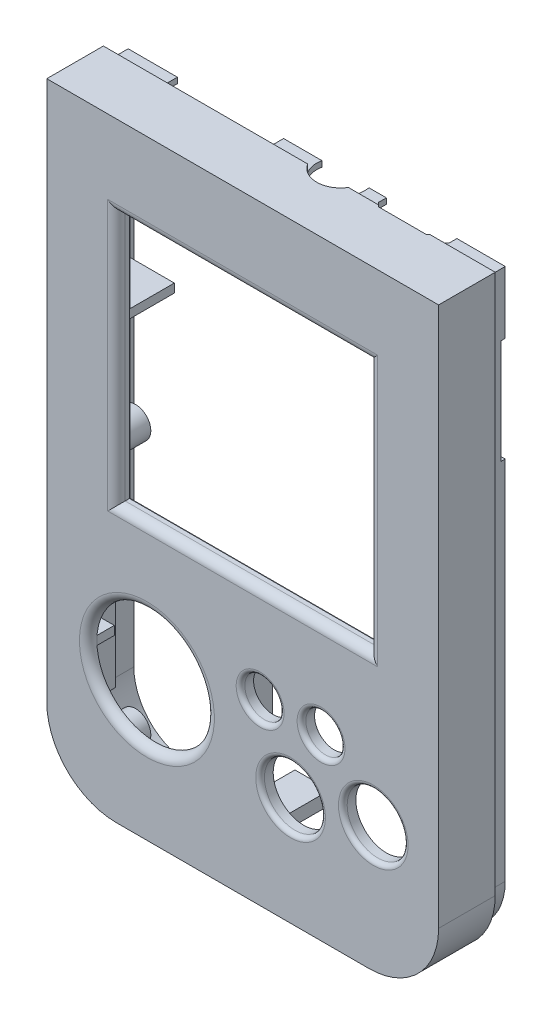
SolidWorks part; units mm, degrees
ref_plane "前视基准面" through (0, 0, 0) normal (0, 0, 1) x (1, 0, 0)
ref_plane "上视基准面" through (0, 0, 0) normal (0, 1, 0) x (1, 0, 0)
ref_plane "右视基准面" through (0, 0, 0) normal (1, 0, 0) x (0, 0, -1)
sketch "草图1" plane through (0, 0, 0) normal (0, 0, 1) x (1, 0, 0)
  line L1 (-45, 70) -> (0, 70)
  line L2 (-45, 70) -> (-45, 8)
  line L3 (-37, 0) -> (-8, 0)
  line L4 (0, 70) -> (0, 8)
  arc A2 (-37, 0) -> (-45, 8) centre (-37, 8) cw
  arc A3 (-8, 0) -> (0, 8) centre (-8, 8) ccw
  point P7 (0, 70)
  point P9 (-45, 0)
  point P10 (-45, 70)
  point P13 (0, 0)
  dimension "D3" = 8
  dimension "D1" = 45
  dimension "D2" = 70
extrude "凸台-拉伸1" add sketch "草图1" along normal blind 8.5 contours L1 L4 A3 L3 A2 L2
shell "抽壳2" thickness 1.5
sketch "草图4" plane through (0, 0, 0) normal (0, 0, -1) x (-1, 0, 0)
  line L0 (22.5, 68.5) -> (22.5, 50068.5) construction
  line L1 (8, 60.5) -> (37, 60.5)
  line L2 (8, 60.5) -> (8, 31.5)
  line L3 (8, 31.5) -> (37, 31.5)
  line L4 (37, 60.5) -> (37, 31.5)
  line L5 (43.5, 68.5) -> (1.5, 68.5) construction
  line L6 (45, 70) -> (0, 70) construction
  line L7 (45, 70) -> (45, 8) construction
  line L8 (0, 70) -> (0, 8) construction
  circle A0 centre (33.5, 16) radius 6.75
  circle A1 centre (7.5, 14.5) radius 3.5
  circle A2 centre (17, 12.5) radius 3.5
  circle A3 centre (13.5, 20.5) radius 2.25
  circle A4 centre (20.5, 20.5) radius 2.25
  point P8 (22.5, 68.5)
  dimension "D4" = 13.5
  dimension "D7" = 7
  dimension "D8" = 7
  dimension "D13" = 4.5
  dimension "D14" = 4.5
  dimension "D1" = 29
  dimension "D2" = 29
  dimension "D3" = 9.5
  dimension "D5" = 11.5
  dimension "D6" = 54
  dimension "D9" = 7.5
  dimension "D10" = 17
  dimension "D11" = 2
  dimension "D12" = 3.5
  dimension "D15" = 8
  dimension "D16" = 7
  dimension "D17" = 13.5
extrude "切除-拉伸3" cut sketch "草图4" against normal through all
fillet "圆角1" radius 1 4 edges at (-22.5, 60.5, 8.5) (-8, 46, 8.5) (-22.5, 31.5, 8.5) (-37, 46, 8.5)
fillet "圆角2" radius 1 1 edges at (-40.25, 16, 8.5)
fillet "圆角3" radius 0.5 4 edges at (-15.75, 20.5, 8.5) (-22.75, 20.5, 8.5) (-11, 14.5, 8.5) (-20.5, 12.5, 8.5)
sketch "草图5" plane through (0, 0, 7) normal (0, 0, -1) x (-1, 0, 0)
  line L1 (6.65, 65.75) -> (38.35, 65.75)
  line L2 (6.65, 65.75) -> (6.65, 30.15)
  line L3 (6.65, 30.15) -> (38.35, 30.15)
  line L4 (38.35, 65.75) -> (38.35, 30.15)
  line L6 (22.5, 55.8413) -> (22.5, 50055.8413) construction
  line L7 (8, 31.5) -> (8, 60.5) construction
  line L8 (37, 60.5) -> (37, 31.5) construction
  line L9 (37, 31.5) -> (8, 31.5) construction
  line L10 (39.35, 66.75) -> (39.35, 29.15)
  line L11 (5.65, 29.15) -> (39.35, 29.15)
  line L12 (5.65, 66.75) -> (5.65, 29.15)
  line L13 (5.65, 66.75) -> (39.35, 66.75)
  dimension "D1" = 31.7
  dimension "D2" = 35.6
  dimension "D3" = 1.35
  dimension "D4" = 1
extrude "凸台-拉伸2" add sketch "草图5" along normal blind 1.4
sketch "草图6" plane through (0, 0, 7) normal (0, 0, -1) x (-1, 0, 0)
  line L0 (45, 70) -> (0, 70) construction
  line L1 (0, 70) -> (0, 8) construction
  line L2 (4.5, 65.5) -> (4.5, 35.25) construction
  line L3 (22.5, -955.0295) -> (22.5, 49044.9705) construction
  line L4 (45, 70) -> (45, 8) construction
  circle A0 centre (4.5, 65.5) radius 1.75
  circle A1 centre (4.5, 65.5) radius 0.75
  circle A2 centre (4.5, 35.25) radius 1.75
  circle A3 centre (4.5, 35.25) radius 0.75
  circle A4 centre (4.5, 5) radius 1.75
  circle A5 centre (4.5, 5) radius 0.75
  circle A6 centre (40.5, 5) radius 0.75
  circle A7 centre (40.5, 5) radius 1.75
  circle A8 centre (40.5, 35.25) radius 0.75
  circle A9 centre (40.5, 35.25) radius 1.75
  circle A10 centre (40.5, 65.5) radius 0.75
  circle A11 centre (40.5, 65.5) radius 1.75
  dimension "D1" = 3.5
  dimension "D4" = 1
  dimension "D2" = 4.5
  dimension "D3" = 4.5
  dimension "D6" = 30.25
  dimension "D5" = 3
extrude "凸台-拉伸3" add sketch "草图6" along normal blind 4.2
sketch "草图7" plane through (0, 0, 0) normal (0, 0, -1) x (-1, 0, 0)
  line L0 (45, 70) -> (45, 8) construction
  line L1 (0, 70) -> (45, 70)
  line L2 (0, 70) -> (0, 8)
  line L3 (8, 0) -> (37, 0)
  line L4 (45, 70) -> (45, 8)
  line L5 (37, 0) -> (8, 0) construction
  line L6 (0.85, 69.15) -> (44.15, 69.15)
  line L7 (44.15, 69.15) -> (44.15, 8)
  line L8 (8, 0.85) -> (37, 0.85)
  line L9 (0.85, 69.15) -> (0.85, 8)
  arc A0 (37, 0) -> (45, 8) centre (37, 8) ccw
  arc A1 (0, 8) -> (8, 0) centre (8, 8) ccw
  arc A2 (37, 0.85) -> (44.15, 8) centre (37, 8) ccw
  arc A3 (0.85, 8) -> (8, 0.85) centre (8, 8) ccw
  dimension "D1" = 8
  dimension "D2" = 0.85
extrude "切除-拉伸4" cut sketch "草图7" against normal blind 2
sketch "草图8" plane through (0, 0, 0) normal (0, 0, -1) x (-1, 0, 0)
  line L0 (0.85, 69.15) -> (0.85, 8) construction
  line L1 (0.85, 62) -> (1.5, 62)
  line L2 (0.85, 62) -> (0.85, 50)
  line L3 (0.85, 50) -> (1.5, 50)
  line L4 (1.5, 62) -> (1.5, 50)
  line L5 (1.5, 68.5) -> (1.5, 8) construction
  line L6 (45, 70) -> (0, 70) construction
  dimension "D1" = 8
  dimension "D2" = 12
extrude "切除-拉伸5" cut sketch "草图8" against normal blind 0.5
sketch "草图9" plane through (0, 0, 7) normal (0, 0, -1) x (-1, 0, 0)
  line L0 (43.5, 68.5) -> (43.5, 8) construction
  line L1 (43.5, 49) -> (38.35, 49)
  line L2 (43.5, 49) -> (43.5, 48)
  line L3 (43.5, 48) -> (38.35, 48)
  line L4 (38.35, 49) -> (38.35, 48)
  line L5 (38.35, 30.15) -> (38.35, 65.75) construction
  line L6 (45, 70) -> (0, 70) construction
  line L7 (37, 1.5) -> (8, 1.5) construction
  line L8 (20.5, 7.5) -> (24.5, 7.5)
  line L9 (20.5, 7.5) -> (20.5, 6)
  line L10 (20.5, 6) -> (24.5, 6)
  line L11 (24.5, 7.5) -> (24.5, 6)
  line L12 (22.5, -944.5131) -> (22.5, 49055.4869) construction
  line L13 (0, 70) -> (0, 8) construction
  line L14 (45, 70) -> (45, 8) construction
  dimension "D1" = 21
  dimension "D2" = 1
  dimension "D3" = 4
  dimension "D4" = 1.5
  dimension "D5" = 4.5
extrude "凸台-拉伸4" add sketch "草图9" along normal blind 6.5
sketch "草图10" plane through (0, 70, 0) normal (0, 1, 0) x (1, 0, 0)
  line L1 (0, -8.5) -> (0, -2) construction
  line L2 (-44.15, 0) -> (-0.85, 0) construction
  line L3 (-38.5, 0) -> (-26.3, 0)
  line L4 (-38.5, 0) -> (-38.5, -1.8)
  line L5 (-38.5, -1.8) -> (-26.3, -1.8)
  line L6 (-26.3, 0) -> (-26.3, -1.8)
  line L7 (-45, -8.5) -> (-45, -2) construction
  line L8 (-14.5, 0) -> (-6.4, 0)
  line L9 (-6.4, 0) -> (-6.4, -0.9)
  line L10 (-6.4, -0.9) -> (-7.7, -2.2)
  line L11 (-7.7, -2.2) -> (-13.2, -2.2)
  line L12 (-13.2, -2.2) -> (-14.5, -0.9)
  line L13 (-14.5, -0.9) -> (-14.5, 0)
  line L14 (-45, -2) -> (0, -2) construction
  line L15 (-37, 0) -> (-8, 0) construction
  circle A0 centre (-19.2, -0.55) radius 2.75
  dimension "D1" = 5.5
  dimension "D2" = 0.55
  dimension "D3" = 19.2
  dimension "D4" = 6.5
  dimension "D5" = 12.2
  dimension "D6" = 1.8
  dimension "D7" = 6.4
  dimension "D8" = 8.1
  dimension "D9" = 2.2
  dimension "D10" = 45
  dimension "D11" = 0.9
extrude "切除-拉伸6" cut sketch "草图10" against normal blind 1.5
sketch "Sketch1" plane through (0, 0, 7) normal (0, 0, -1) x (-1, 0, 0)
  circle A0 centre (33.5, 16) radius 8.25
  circle A1 centre (33.5, 16) radius 6.75 construction
  dimension "D1" = 16.5
extrude "Cut-Extrude1" cut sketch "Sketch1" against normal blind 0.5
sketch "Sketch2" plane through (0, 0, 7.5) normal (0, 0, -1) x (-1, 0, 0)
  line L0 (-965.6843, 16) -> (49034.3157, 16) construction
  line L1 (24.75, 16.5) -> (26.75, 16.5)
  line L2 (24.75, 16.5) -> (24.75, 15.5)
  line L3 (24.75, 15.5) -> (26.75, 15.5)
  line L4 (26.75, 16.5) -> (26.75, 15.5)
  line L5 (40.25, 16.5) -> (42.25, 16.5)
  line L6 (40.25, 16.5) -> (40.25, 15.5)
  line L7 (40.25, 15.5) -> (42.25, 15.5)
  line L8 (42.25, 16.5) -> (42.25, 15.5)
  line L9 (33.5, -982.1684) -> (33.5, 49017.8316) construction
  circle A1 centre (33.5, 16) radius 6.75 construction
  point P11 (33.5, 16)
  dimension "D1" = 1
  dimension "D2" = 13.5
  dimension "D3" = 2
extrude "Boss-Extrude1" add sketch "Sketch2" along normal blind 2
sketch "草图12" plane through (0, 0, 7) normal (0, 0, -1) x (-1, 0, 0)
  line L0 (43.5, 48) -> (43.5, 8) construction
  line L1 (24, 23.5) -> (25, 23.5)
  line L2 (24, 23.5) -> (24, 8.5)
  line L3 (24, 8.5) -> (25, 8.5)
  line L4 (25, 23.5) -> (25, 8.5)
  line L5 (43.5, 23.5) -> (42, 23.5)
  line L6 (43.5, 23.5) -> (43.5, 8.5)
  line L7 (43.5, 8.5) -> (42, 8.5)
  line L8 (42, 23.5) -> (42, 8.5)
  line L9 (1.5, 50) -> (1.5, 8) construction
  line L10 (1.5, 23.5) -> (3, 23.5)
  line L11 (1.5, 23.5) -> (1.5, 8.5)
  line L12 (1.5, 8.5) -> (3, 8.5)
  line L13 (3, 23.5) -> (3, 8.5)
  line L14 (-973.25, 16) -> (49026.75, 16) construction
  line L15 (26.75, 15.5) -> (26.75, 16.5) construction
  arc A0 (26.75, 16) -> (40.25, 16) centre (33.5, 16) ccw construction
  point P25 (26.75, 16)
  dimension "D1" = 1.5
  dimension "D2" = 1
  dimension "D3" = 15
  dimension "D4" = 8.5
extrude "凸台-拉伸5" add sketch "草图12" along normal blind 3.4
